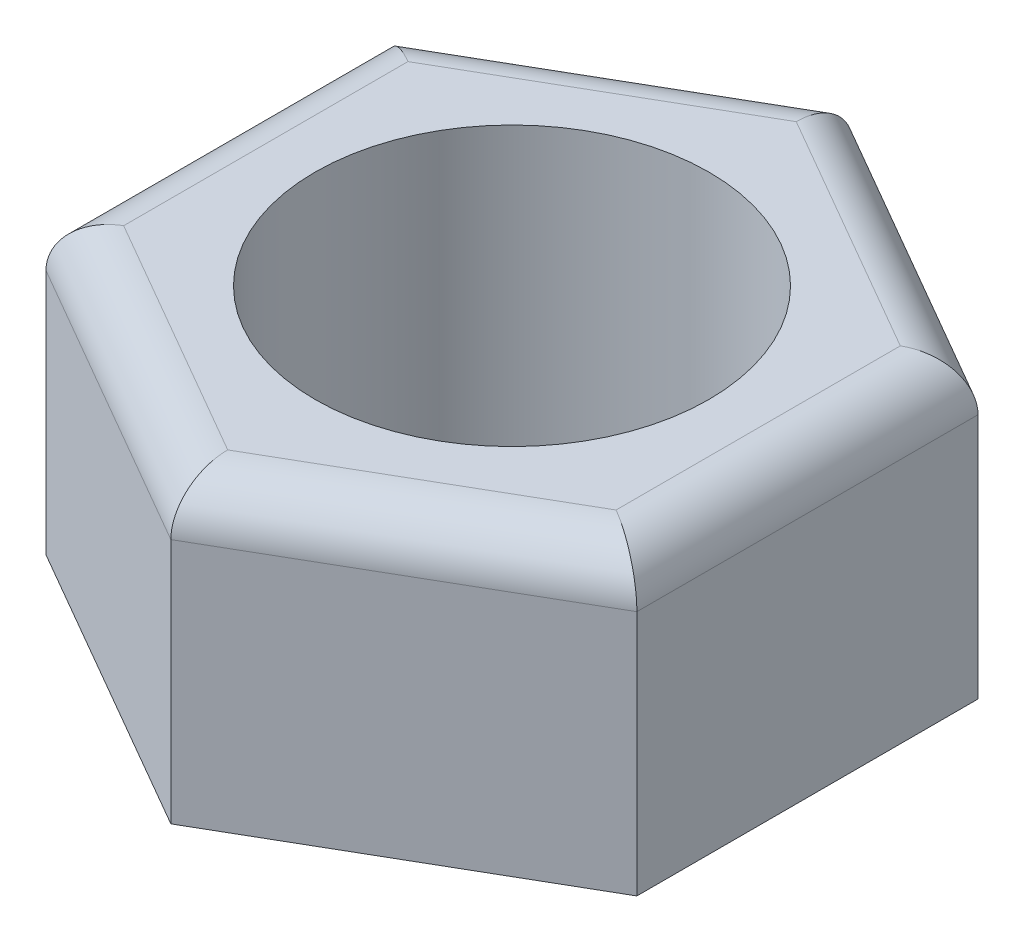
SolidWorks part; units mm, degrees
ref_plane "Front Plane" through (0, 0, 0) normal (0, 0, 1) x (1, 0, 0)
ref_plane "Top Plane" through (0, 0, 0) normal (0, 1, 0) x (1, 0, 0)
ref_plane "Right Plane" through (0, 0, 0) normal (1, 0, 0) x (0, 0, -1)
sketch "Sketch1" plane through (0, 0, 0) normal (0, 1, 0) x (1, 0, 0)
  line L1 (0, 1.7321) -> (-1.5, 0.866)
  line L2 (-1.5, 0.866) -> (-1.5, -0.866)
  line L3 (-1.5, -0.866) -> (0, -1.7321)
  line L4 (0, -1.7321) -> (1.5, -0.866)
  line L5 (1.5, -0.866) -> (1.5, 0.866)
  line L6 (1.5, 0.866) -> (0, 1.7321)
  circle A0 centre (0, 0) radius 1
  circle A1 centre (0, 0) radius 1.5 construction
  dimension "D1" = 2
  dimension "D2" = 3
extrude "Boss-Extrude1" add sketch "Sketch1" along normal blind 1.5
fillet "Fillet1" radius 0.25 6 edges at (0.75, 1.5, -1.299) (-0.75, 1.5, -1.299) (-1.5, 1.5, 0) (-0.75, 1.5, 1.299) (0.75, 1.5, 1.299) (1.5, 1.5, 0)
